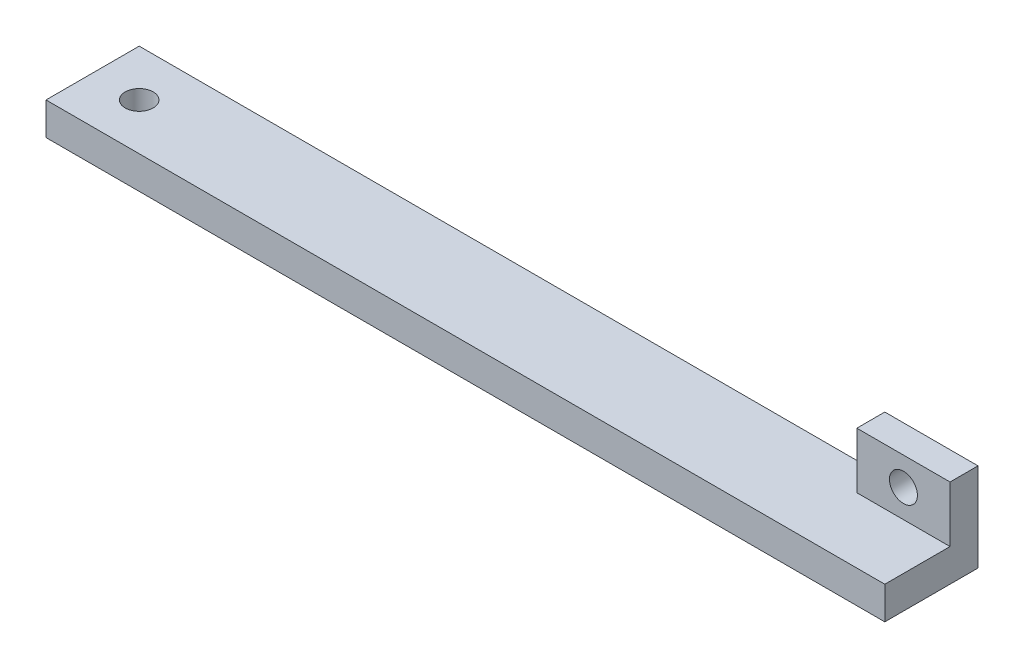
SolidWorks part; units mm, degrees
ref_plane "Front Plane" through (0, 0, 0) normal (0, 0, 1) x (1, 0, 0)
ref_plane "Top Plane" through (0, 0, 0) normal (0, 1, 0) x (1, 0, 0)
ref_plane "Right Plane" through (0, 0, 0) normal (1, 0, 0) x (0, 0, -1)
sketch "Sketch1" plane through (0, 0, 0) normal (0, 1, 0) x (1, 0, 0)
  line L1 (-45, 5) -> (45, 5)
  line L2 (-45, 5) -> (-45, -5)
  line L3 (-45, -5) -> (45, -5)
  line L4 (45, 5) -> (45, -5)
  line L5 (-45, 5) -> (45, -5) construction
  line L6 (-45, -5) -> (45, 5) construction
  circle A0 centre (-40, 0) radius 1.5
  point P0 (0, 0)
  dimension "D3" = 5
  dimension "D1" = 10
  dimension "D2" = 90
extrude "Boss-Extrude1" add sketch "Sketch1" along normal blind 3.5
sketch "Sketch2" plane through (0, 3.5, 0) normal (0, 1, 0) x (1, 0, 0)
  line L8 (45, 5) -> (35, 5)
  line L9 (45, 5) -> (45, 2)
  line L10 (45, 2) -> (35, 2)
  line L11 (35, 5) -> (35, 2)
  dimension "D3" = 3
extrude "Boss-Extrude2" add sketch "Sketch2" along normal blind 6
sketch "Sketch3" plane through (0, 0, -2) normal (0, 0, 1) x (1, 0, 0)
  circle A0 centre (40, 6.5) radius 1.5
extrude "Cut-Extrude1" cut sketch "Sketch3" against normal blind 3
